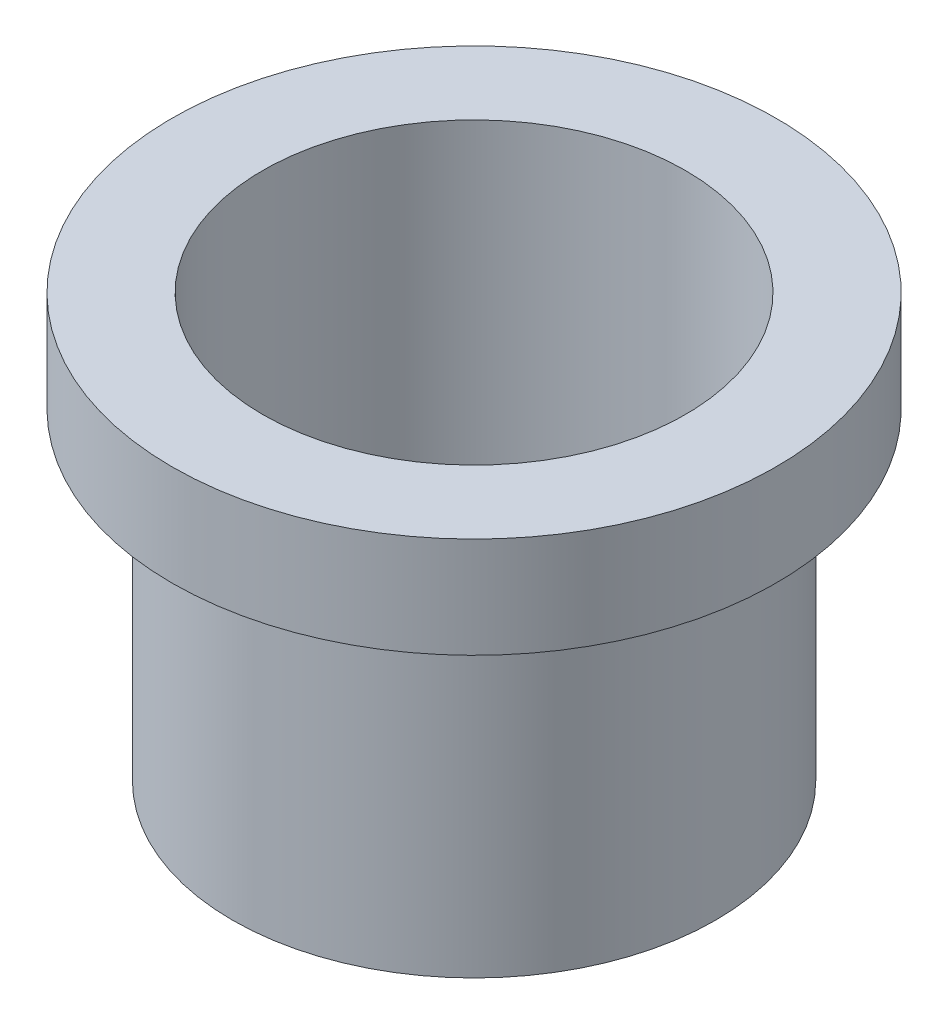
SolidWorks part; units mm, degrees
ref_plane "Front Plane" through (0, 0, 0) normal (0, 0, 1) x (1, 0, 0)
ref_plane "Top Plane" through (0, 0, 0) normal (0, 1, 0) x (1, 0, 0)
ref_plane "Right Plane" through (0, 0, 0) normal (1, 0, 0) x (0, 0, -1)
sketch "Sketch1" plane through (0, 0, 0) normal (0, 0, 1) x (1, 0, 0)
  line L0 (0, 64.7505) -> (0, -45.0483) construction
  line L1 (0, 21) -> (15, 21)
  line L2 (15, 21) -> (15, 16)
  line L3 (15, 16) -> (12, 16)
  line L4 (12, 16) -> (12, 0)
  line L5 (12, 0) -> (0, 0)
  line L6 (0, 0) -> (0, 21)
  dimension "D1" = 15
  dimension "D2" = 12
  dimension "D3" = 16
  dimension "D4" = 21
revolve "Revolve1" add sketch "Sketch1" angle 360 about L0
sketch "Sketch2" plane through (0, 21, 0) normal (0, 1, 0) x (1, 0, 0)
  circle A0 centre (0, 0) radius 10.5
  dimension "D1" = 21
extrude "Cut-Extrude2" cut sketch "Sketch2" against normal through all
